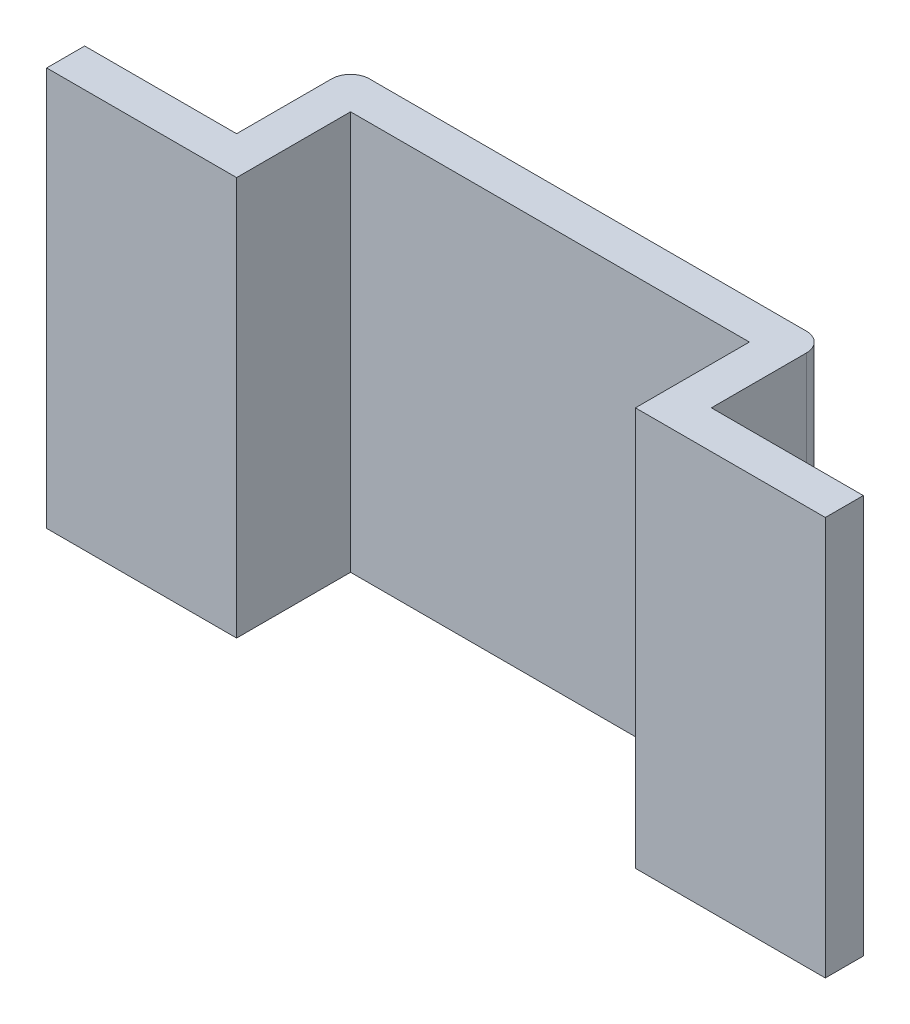
SolidWorks part; units mm, degrees
ref_plane "Front Plane" through (0, 0, 0) normal (0, 0, 1) x (1, 0, 0)
ref_plane "Top Plane" through (0, 0, 0) normal (0, 1, 0) x (1, 0, 0)
ref_plane "Right Plane" through (0, 0, 0) normal (1, 0, 0) x (0, 0, -1)
sketch "Sketch1" plane through (0, 0, 0) normal (0, 1, 0) x (1, 0, 0)
  line L0 (-10.5, 0) -> (-20.5, 0)
  line L1 (-20.5, 0) -> (-20.5, 2)
  line L2 (-20.5, 2) -> (-12.5, 2)
  line L3 (-12.5, 2) -> (-12.5, 8)
  line L4 (-12.5, 8) -> (12.5, 8)
  line L5 (-10.5, 0) -> (-10.5, 6)
  line L6 (-10.5, 6) -> (10.5, 6)
  line L7 (0, 8) -> (0, 0) construction
  line L8 (10.5, 0) -> (10.5, 6)
  line L9 (12.5, 2) -> (12.5, 8)
  line L10 (20.5, 2) -> (12.5, 2)
  line L11 (20.5, 0) -> (20.5, 2)
  line L12 (10.5, 0) -> (20.5, 0)
  point P6 (0, 0)
  point P11 (0, 6)
  dimension "D1" = 10
  dimension "D2" = 10.5
  dimension "D3" = 2
  dimension "D4" = 2
  dimension "D5" = 2
  dimension "D6" = 6
extrude "Boss-Extrude1" add sketch "Sketch1" along normal blind 21
fillet "Fillet1" radius 1 2 edges at (12.5, 10.5, -8) (-12.5, 10.5, -8)
